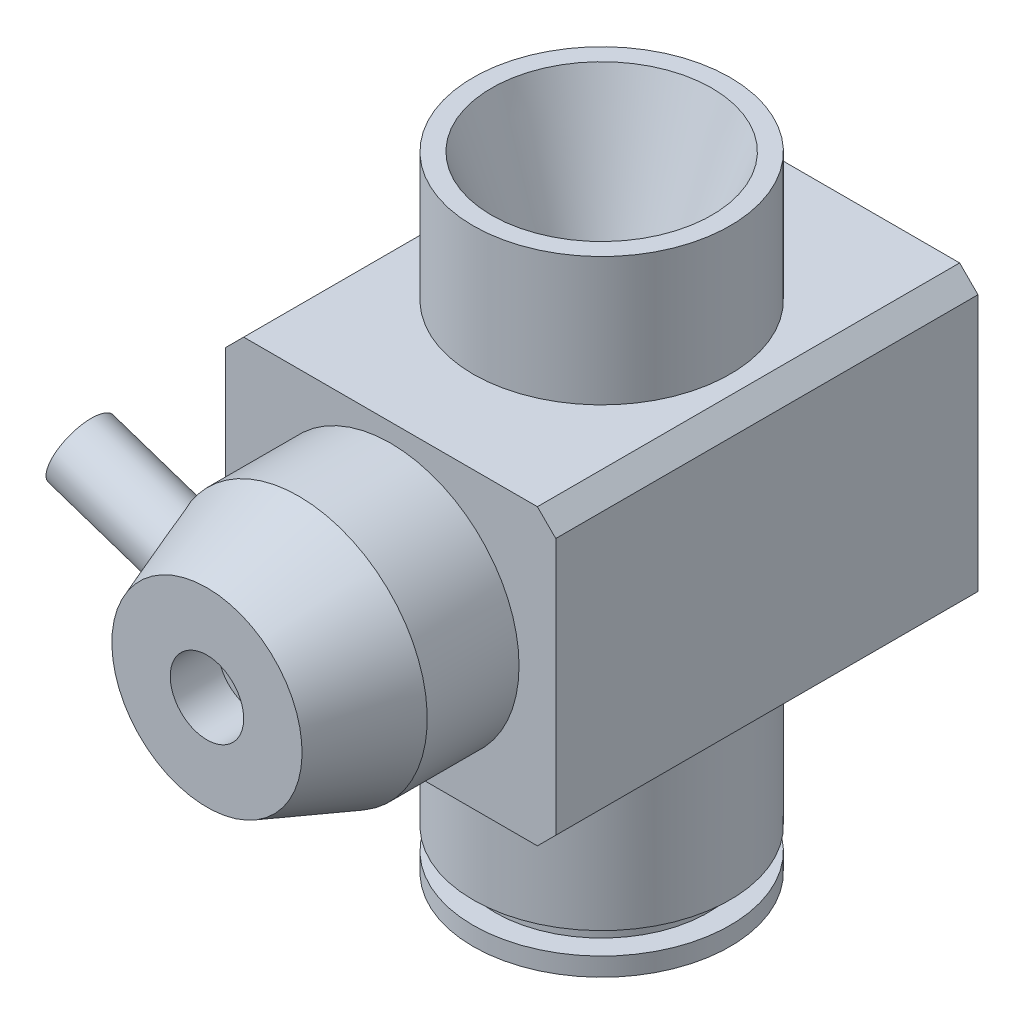
SolidWorks part; units mm, degrees
ref_plane "Face" through (0, 0, 0) normal (0, 0, 1) x (1, 0, 0)
ref_plane "Dessus" through (0, 0, 0) normal (0, 1, 0) x (1, 0, 0)
ref_plane "Droite" through (0, 0, 0) normal (1, 0, 0) x (0, 0, -1)
sketch "Esquisse1" plane through (0, 0, 0) normal (0, 0, 1) x (1, 0, 0)
  line L0 (-9, 16) -> (-9, 0)
  line L1 (-9, 0) -> (9, 0)
  line L3 (-9, 16) -> (9, 16)
  line L4 (9, 0) -> (9, 16)
  circle A0 centre (0, 8) radius 6
  dimension "D5" = 12
  dimension "D1" = 16
  dimension "D2" = 9
  dimension "D3" = 18
  dimension "D4" = 8
extrude "Base-Extrusion" add sketch "Esquisse1" along normal mid plane 23
sketch "Esquisse5" plane through (0, 0, 0) normal (1, 0, 0) x (0, 0, -1)
  line L0 (0, 26.536) -> (0, -13.9946) construction
  line L2 (7, -10) -> (7, -11)
  line L3 (3.5064, 0) -> (7, 0)
  line L4 (7, -8.8) -> (5.8, -8.8)
  line L5 (5.5, -11) -> (7, -11)
  line L6 (7, 0) -> (7, -8.8)
  line L7 (-11.5, 16) -> (11.5, 16) construction
  line L8 (7, -10) -> (5.8, -10)
  line L9 (5.8, -8.8) -> (5.8, -10)
  line L10 (3.5064, 0) -> (5.5, -11)
  line L11 (7, 16) -> (3.5, 16)
  line L12 (7, 16) -> (7, 23)
  line L13 (7, 23) -> (6, 23)
  line L15 (6, 23) -> (3.5, 16)
  dimension "D1" = 7
  dimension "D2" = 11
  dimension "D3" = 1.2
  dimension "D4" = 1.2
  dimension "D5" = 1
  dimension "D6" = 5.5
  dimension "D7" = 7
  dimension "D8" = 7
  dimension "D9" = 1
  dimension "D10" = 3.5
revolve "Boss.-Révol.1" add sketch "Esquisse5" angle 360 about L0
sketch "Esquisse6" plane through (0, 0, 0) normal (0, -1, 0) x (1, 0, 0)
  circle A1 centre (0, 0) radius 3.5064
  circle A2 centre (0, 0) radius 3.5064
  dimension "D1" = 0
extrude "Enlèv. mat.-Extru.1" cut sketch "Esquisse6" against normal through all
sketch "Esquisse8" plane through (0, 0, 0) normal (1, 0, 0) x (0, 0, -1)
  line L0 (-5.7893, 8) -> (-24.1042, 8) construction
  line L1 (-11.5, 15) -> (-16.5, 15)
  line L2 (-5.5749, 9.8) -> (-11.5, 9.8)
  line L3 (-5.5749, 9.8) -> (-5.5749, 9)
  line L4 (-5.5749, 9) -> (-18.8946, 9)
  line L5 (-18.8946, 9) -> (-18.8946, 10)
  line L6 (-11.5, 0) -> (-11.5, 16) construction
  line L7 (-16.5, 15) -> (-21.5, 13.1801)
  line L8 (-21.5, 13.1801) -> (-21.5, 10)
  line L9 (-11.5, 15) -> (-11.5, 9.8)
  line L10 (-18.8946, 10) -> (-21.5, 10)
  dimension "D1" = 8
  dimension "D2" = 5
  dimension "D3" = 7
  dimension "D4" = 1
  dimension "D5" = 0.8
  dimension "D6" = 20
  dimension "D7" = 10
  dimension "D8" = 2
revolve "Boss.-Révol.2" add sketch "Esquisse8" angle 360 about L0
chamfer "Chanfrein1" distance 1 angle 45 4 edges at (9, 16, 0) (9, 0, 0) (-9, 0, 0) (-9, 16, 0)
ref_plane "Plan1" through (2.4073, 7.1945, 0) normal (0.3173, 0.9483, 0) x (-0.9483, 0.3173, 0)
sketch "Esquisse9" plane through (2.4073, 7.1945, 0) normal (0.3173, 0.9483, 0) x (-0.9483, 0.3173, 0)
  line L0 (2.5384, 17) -> (19.601, 17) construction
  line L1 (2.5384, 5.7893) -> (2.5384, 24.1042) construction
  line L2 (2.5384, 11.5) -> (2.5384, -11.5) construction
  line L3 (14.5384, 17) -> (14.5384, 18.8)
  line L4 (14.5384, 18.8) -> (6.9794, 18.8)
  line L5 (6.9794, 17) -> (6.9794, 18.8)
  line L6 (14.5384, 17) -> (6.9794, 17)
  line L7 (8.42, 0) -> (-4.4406, 0) construction
  dimension "D1" = 1.8
  dimension "D2" = 12
  dimension "D3" = 17
revolve "Boss.-Révol.3" add sketch "Esquisse9" angle 360 about L0
sketch "Esquisse10" plane through (-13.7871, 4.6131, 0) normal (-0.9483, 0.3173, 0) x (0, 0, 1)
  circle A0 centre (17, 7.5866) radius 1
  dimension "D1" = 2
extrude "Enlèv. mat.-Extru.2" cut sketch "Esquisse10" against normal up to next
